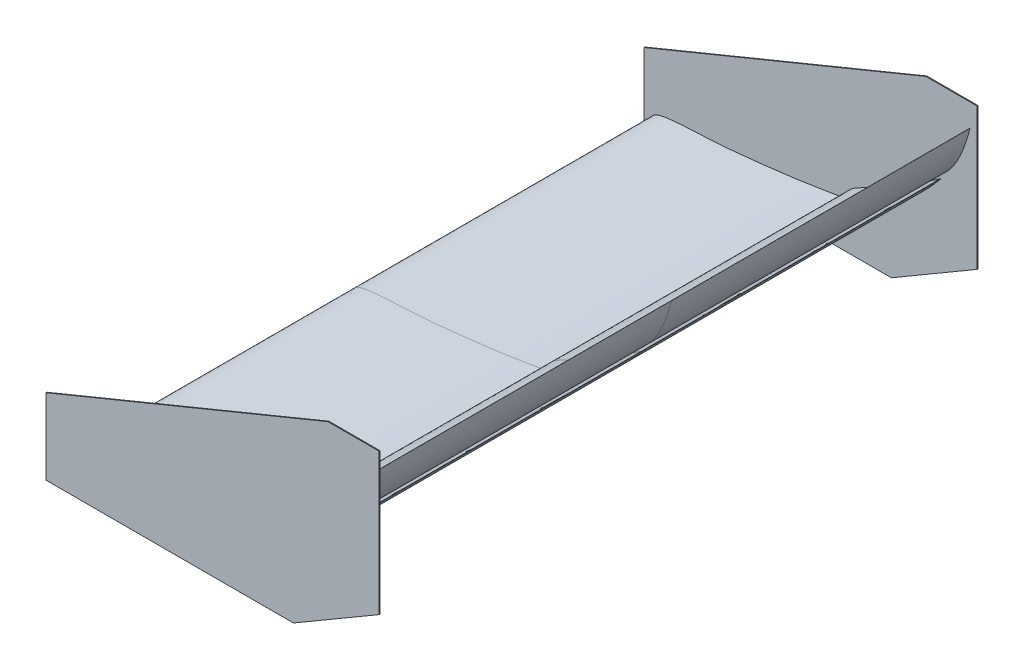
SolidWorks part; units mm, degrees
ref_plane "Front Plane" through (0, 0, 0) normal (0, 0, 1) x (1, 0, 0)
ref_plane "Top Plane" through (0, 0, 0) normal (0, 1, 0) x (1, 0, 0)
ref_plane "Right Plane" through (0, 0, 0) normal (1, 0, 0) x (0, 0, -1)
curve "Curve1"
  spline degree 3 poles (99.0688, 13.798, 0) (98.985, 13.7552, 0) (98.6508, 13.5849, 0) (97.9029, 13.2032, 0) (96.6609, 12.5823, 0) (94.9376, 11.7325, 0) (92.7448, 10.6803, 0) (90.1008, 9.4515, 0) (87.0291, 8.0763, 0) (83.5562, 6.5881, 0) (79.7145, 5.0216, 0) (75.5395, 3.4142, 0) (71.0738, 1.7976, 0) (66.3611, 0.21, 0) (61.4497, -1.3148, 0) (56.392, -2.7475, 0) (51.2426, -4.0574, 0) (46.0551, -5.2184, 0) (40.854, -6.233, 0) (35.6813, -6.9933, 0) (30.6038, -7.449, 0) (25.7295, -7.6105, 0) (21.1262, -7.4993, 0) (16.8578, -7.1394, 0) (12.9825, -6.5696, 0) (9.5507, -5.8327, 0) (6.6043, -4.9721, 0) (4.1763, -4.0324, 0) (2.283, -3.0565, 0) (0.9373, -2.0695, 0) (0.1025, -1.073, 0) (-0.1138, 0.0176, 0) (0.4141, 0.9898, 0) (1.479, 1.7019, 0) (2.9987, 2.2847, 0) (4.9955, 2.7588, 0) (7.4464, 3.142, 0) (10.3255, 3.4469, 0) (13.5973, 3.6931, 0) (17.225, 3.9006, 0) (21.1689, 4.0985, 0) (25.3897, 4.3118, 0) (29.8469, 4.5676, 0) (34.499, 4.8945, 0) (39.3394, 5.3285, 0) (44.3266, 5.8555, 0) (49.4192, 6.3918, 0) (54.5234, 6.9659, 0) (59.5819, 7.5731, 0) (64.5401, 8.2118, 0) (69.3432, 8.8764, 0) (73.9381, 9.5566, 0) (78.2741, 10.2373, 0) (82.3012, 10.9094, 0) (85.9747, 11.5481, 0) (89.2527, 12.1455, 0) (92.092, 12.6747, 0) (94.4753, 13.1478, 0) (96.3297, 13.4752, 0) (97.7415, 13.8436, 0) (98.4673, 13.8401, 0) (98.9864, 14.1185, 0) (99.0172, 13.9649, 0) (99.0268, 13.9173, 0) knots 0 0 0 0 0.001372 0.005465 0.012235 0.021602 0.033461 0.047671 0.064081 0.082496 0.102719 0.124527 0.147676 0.171913 0.196978 0.222597 0.248497 0.274385 0.300041 0.32569 0.350525 0.37428 0.396711 0.417577 0.436654 0.453744 0.46868 0.481329 0.491631 0.499616 0.505546 0.510185 0.514824 0.520702 0.528516 0.538466 0.550543 0.564643 0.580638 0.598345 0.617584 0.638174 0.659922 0.682632 0.706121 0.730727 0.7557 0.780732 0.805564 0.829932 0.85357 0.876213 0.89761 0.917519 0.935698 0.951943 0.966047 0.97784 0.987174 0.993932 0.998018 0.999386 1 1 1 1
sketch "Sketch1" plane through (0, 0, 0) normal (0, 0, 1) x (1, 0, 0)
  line L0 (99.0268, 13.9173) -> (99.0688, 13.798)
  spline S0 degree 3 poles (-1512.6726, 3670.5274) (216.2288, 66.9665) (155.9525, 42.8322) (97.9029, 13.2032) (96.6609, 12.5823) (94.9376, 11.7325) (92.7448, 10.6803) (90.1008, 9.4515) (87.0291, 8.0763) (83.5562, 6.5881) (79.7145, 5.0216) (75.5395, 3.4142) (71.0738, 1.7976) (66.3611, 0.21) (61.4497, -1.3148) (56.392, -2.7475) (51.2426, -4.0574) (46.0551, -5.2184) (40.854, -6.233) (35.6813, -6.9933) (30.6038, -7.449) (25.7295, -7.6105) (21.1262, -7.4993) (16.8578, -7.1394) (12.9825, -6.5696) (9.5507, -5.8327) (6.6043, -4.9721) (4.1763, -4.0324) (2.283, -3.0565) (0.9373, -2.0695) (0.1025, -1.073) (-0.1138, 0.0176) (0.4141, 0.9898) (1.479, 1.7019) (2.9987, 2.2847) (4.9955, 2.7588) (7.4464, 3.142) (10.3255, 3.4469) (13.5973, 3.6931) (17.225, 3.9006) (21.1689, 4.0985) (25.3897, 4.3118) (29.8469, 4.5676) (34.499, 4.8945) (39.3394, 5.3285) (44.3266, 5.8555) (49.4192, 6.3918) (54.5234, 6.9659) (59.5819, 7.5731) (64.5401, 8.2118) (69.3432, 8.8764) (73.9381, 9.5566) (78.2741, 10.2373) (82.3012, 10.9094) (85.9747, 11.5481) (89.2527, 12.1455) (92.092, 12.6747) (94.4753, 13.1478) (96.3297, 13.4752) (97.7415, 13.8436) (98.4673, 13.8401) (101.7659, 15.6087) (62.7437, -56.794) (2072.5985, 3482.5615) knots -0.937364 -0.937364 -0.937364 -0.937364 0.001372 0.005465 0.012235 0.021602 0.033461 0.047671 0.064081 0.082496 0.102719 0.124527 0.147676 0.171913 0.196978 0.222597 0.248497 0.274385 0.300041 0.32569 0.350525 0.37428 0.396711 0.417577 0.436654 0.453744 0.46868 0.481329 0.491631 0.499616 0.505546 0.510185 0.514824 0.520702 0.528516 0.538466 0.550543 0.564643 0.580638 0.598345 0.617584 0.638174 0.659922 0.682632 0.706121 0.730727 0.7557 0.780732 0.805564 0.829932 0.85357 0.876213 0.89761 0.917519 0.935698 0.951943 0.966047 0.97784 0.987174 0.993932 0.998018 0.999386 1.032494 1.032494 1.032494 1.032494 only from (99.0688, 13.798) to (99.0268, 13.9173) construction
  spline S1 degree 3 poles (99.0688, 13.798) (98.985, 13.7552) (98.6508, 13.5849) (97.9029, 13.2032) (96.6609, 12.5823) (94.9376, 11.7325) (92.7448, 10.6803) (90.1008, 9.4515) (87.0291, 8.0763) (83.5562, 6.5881) (79.7145, 5.0216) (75.5395, 3.4142) (71.0738, 1.7976) (66.3611, 0.21) (61.4497, -1.3148) (56.392, -2.7475) (51.2426, -4.0574) (46.0551, -5.2184) (40.854, -6.233) (35.6813, -6.9933) (30.6038, -7.449) (25.7295, -7.6105) (21.1262, -7.4993) (16.8578, -7.1394) (12.9825, -6.5696) (9.5507, -5.8327) (6.6043, -4.9721) (4.1763, -4.0324) (2.283, -3.0565) (0.9373, -2.0695) (0.1025, -1.073) (-0.1138, 0.0176) (0.4141, 0.9898) (1.479, 1.7019) (2.9987, 2.2847) (4.9955, 2.7588) (7.4464, 3.142) (10.3255, 3.4469) (13.5973, 3.6931) (17.225, 3.9006) (21.1689, 4.0985) (25.3897, 4.3118) (29.8469, 4.5676) (34.499, 4.8945) (39.3394, 5.3285) (44.3266, 5.8555) (49.4192, 6.3918) (54.5234, 6.9659) (59.5819, 7.5731) (64.5401, 8.2118) (69.3432, 8.8764) (73.9381, 9.5566) (78.2741, 10.2373) (82.3012, 10.9094) (85.9747, 11.5481) (89.2527, 12.1455) (92.092, 12.6747) (94.4753, 13.1478) (96.3297, 13.4752) (97.7415, 13.8436) (98.4673, 13.8401) (98.9864, 14.1185) (99.0172, 13.9649) (99.0268, 13.9173) knots 0 0 0 0 0.001372 0.005465 0.012235 0.021602 0.033461 0.047671 0.064081 0.082496 0.102719 0.124527 0.147676 0.171913 0.196978 0.222597 0.248497 0.274385 0.300041 0.32569 0.350525 0.37428 0.396711 0.417577 0.436654 0.453744 0.46868 0.481329 0.491631 0.499616 0.505546 0.510185 0.514824 0.520702 0.528516 0.538466 0.550543 0.564643 0.580638 0.598345 0.617584 0.638174 0.659922 0.682632 0.706121 0.730727 0.7557 0.780732 0.805564 0.829932 0.85357 0.876213 0.89761 0.917519 0.935698 0.951943 0.966047 0.97784 0.987174 0.993932 0.998018 0.999386 1 1 1 1
extrude "Boss-Extrude1" add sketch "Sketch1" along normal blind 138.1
curve "Curve2"
  spline degree 3 poles (133.4459, 41.95, 0) (133.4162, 41.9134, 0) (133.2983, 41.7677, 0) (133.0343, 41.4412, 0) (132.5932, 40.905, 0) (131.9789, 40.1664, 0) (131.1913, 39.2398, 0) (130.2335, 38.1408, 0) (129.11, 36.888, 0) (127.8264, 35.5019, 0) (126.3902, 34.0051, 0) (124.81, 32.4219, 0) (123.099, 30.7753, 0) (121.2692, 29.0916, 0) (119.3359, 27.3964, 0) (117.3171, 25.7134, 0) (115.2314, 24.0678, 0) (113.098, 22.4825, 0) (110.9286, 20.9614, 0) (108.7205, 19.5621, 0) (106.4939, 18.3214, 0) (104.3003, 17.2563, 0) (102.175, 16.3709, 0) (100.1521, 15.6673, 0) (98.2661, 15.1394, 0) (96.5487, 14.7781, 0) (95.0278, 14.572, 0) (93.7277, 14.5074, 0) (92.6644, 14.5682, 0) (91.849, 14.7453, 0) (91.265, 15.0307, 0) (90.9445, 15.4849, 0) (90.9878, 16.0363, 0) (91.3294, 16.5781, 0) (91.9051, 17.1534, 0) (92.7207, 17.7761, 0) (93.7623, 18.4495, 0) (95.0154, 19.1743, 0) (96.4598, 19.9522, 0) (98.0746, 20.7847, 0) (99.8359, 21.6772, 0) (101.7205, 22.633, 0) (103.7043, 23.6562, 0) (105.7628, 24.7517, 0) (107.8855, 25.9343, 0) (110.0564, 27.1892, 0) (112.2734, 28.4699, 0) (114.4881, 29.7702, 0) (116.6752, 31.0763, 0) (118.8101, 32.3763, 0) (120.8689, 33.6567, 0) (122.8294, 34.9019, 0) (124.6715, 36.0946, 0) (126.3743, 37.2206, 0) (127.9224, 38.2594, 0) (129.2982, 39.1989, 0) (130.4875, 40.018, 0) (131.4799, 40.7188, 0) (132.2604, 41.2455, 0) (132.8303, 41.7009, 0) (133.1625, 41.8469, 0) (133.343, 42.0796, 0) (133.3884, 42.0158, 0) (133.4024, 41.996, 0) knots 0 0 0 0 0.001372 0.005465 0.012235 0.021602 0.033461 0.047671 0.064081 0.082496 0.102719 0.124527 0.147676 0.171913 0.196978 0.222597 0.248497 0.274385 0.300041 0.32569 0.350525 0.37428 0.396711 0.417577 0.436654 0.453744 0.46868 0.481329 0.491631 0.499616 0.505546 0.510185 0.514824 0.520702 0.528516 0.538466 0.550543 0.564643 0.580638 0.598345 0.617584 0.638174 0.659922 0.682632 0.706121 0.730727 0.7557 0.780732 0.805564 0.829932 0.85357 0.876213 0.89761 0.917519 0.935698 0.951943 0.966047 0.97784 0.987174 0.993932 0.998018 0.999386 1 1 1 1
sketch "Sketch2" plane through (0, 0, 0) normal (0, 0, 1) x (1, 0, 0)
  line L0 (133.4022, 41.9963) -> (133.4459, 41.95)
  spline S0 degree 3 poles (-2110.8187, 2030.7967) (182.5864, 96.5513) (156.3853, 70.3189) (133.0343, 41.4412) (132.5932, 40.905) (131.9789, 40.1664) (131.1913, 39.2398) (130.2335, 38.1408) (129.11, 36.888) (127.8264, 35.5019) (126.3902, 34.0051) (124.81, 32.4219) (123.099, 30.7753) (121.2692, 29.0916) (119.3359, 27.3964) (117.3171, 25.7134) (115.2314, 24.0678) (113.098, 22.4825) (110.9286, 20.9614) (108.7205, 19.5621) (106.4939, 18.3214) (104.3003, 17.2563) (102.175, 16.3709) (100.1521, 15.6673) (98.2661, 15.1394) (96.5487, 14.7781) (95.0278, 14.572) (93.7277, 14.5074) (92.6644, 14.5682) (91.849, 14.7453) (91.265, 15.0307) (90.9445, 15.4849) (90.9878, 16.0363) (91.3294, 16.5781) (91.9051, 17.1534) (92.7207, 17.7761) (93.7623, 18.4495) (95.0154, 19.1743) (96.4598, 19.9522) (98.0746, 20.7847) (99.8359, 21.6772) (101.7205, 22.633) (103.7043, 23.6562) (105.7628, 24.7517) (107.8855, 25.9343) (110.0564, 27.1892) (112.2734, 28.4699) (114.4881, 29.7702) (116.6752, 31.0763) (118.8101, 32.3763) (120.8689, 33.6567) (122.8294, 34.9019) (124.6715, 36.0946) (126.3743, 37.2206) (127.9224, 38.2594) (129.2982, 39.1989) (130.4875, 40.018) (131.4799, 40.7188) (132.2604, 41.2455) (132.8303, 41.7009) (133.1625, 41.8469) (134.4499, 43.5066) (130.284, -9.7014) (427.082, 3025.7492) knots -1.069969 -1.069969 -1.069969 -1.069969 0.001372 0.005465 0.012235 0.021602 0.033461 0.047671 0.064081 0.082496 0.102719 0.124527 0.147676 0.171913 0.196978 0.222597 0.248497 0.274385 0.300041 0.32569 0.350525 0.37428 0.396711 0.417577 0.436654 0.453744 0.46868 0.481329 0.491631 0.499616 0.505546 0.510185 0.514824 0.520702 0.528516 0.538466 0.550543 0.564643 0.580638 0.598345 0.617584 0.638174 0.659922 0.682632 0.706121 0.730727 0.7557 0.780732 0.805564 0.829932 0.85357 0.876213 0.89761 0.917519 0.935698 0.951943 0.966047 0.97784 0.987174 0.993932 0.998018 0.999386 1.037213 1.037213 1.037213 1.037213 only from (133.4459, 41.95) to (133.4024, 41.996) construction
  spline S1 degree 3 poles (133.4459, 41.95) (133.4162, 41.9134) (133.2983, 41.7677) (133.0343, 41.4412) (132.5932, 40.905) (131.9789, 40.1664) (131.1913, 39.2398) (130.2335, 38.1408) (129.11, 36.888) (127.8264, 35.5019) (126.3902, 34.0051) (124.81, 32.4219) (123.099, 30.7753) (121.2692, 29.0916) (119.3359, 27.3964) (117.3171, 25.7134) (115.2314, 24.0678) (113.098, 22.4825) (110.9286, 20.9614) (108.7205, 19.5621) (106.4939, 18.3214) (104.3003, 17.2563) (102.175, 16.3709) (100.1521, 15.6673) (98.2661, 15.1394) (96.5487, 14.7781) (95.0278, 14.572) (93.7277, 14.5074) (92.6644, 14.5682) (91.849, 14.7453) (91.265, 15.0307) (90.9445, 15.4849) (90.9878, 16.0363) (91.3294, 16.5781) (91.9051, 17.1534) (92.7207, 17.7761) (93.7623, 18.4495) (95.0154, 19.1743) (96.4598, 19.9522) (98.0746, 20.7847) (99.8359, 21.6772) (101.7205, 22.633) (103.7043, 23.6562) (105.7628, 24.7517) (107.8855, 25.9343) (110.0564, 27.1892) (112.2734, 28.4699) (114.4881, 29.7702) (116.6752, 31.0763) (118.8101, 32.3763) (120.8689, 33.6567) (122.8294, 34.9019) (124.6715, 36.0946) (126.3743, 37.2206) (127.9224, 38.2594) (129.2982, 39.1989) (130.4875, 40.018) (131.4799, 40.7188) (132.2604, 41.2455) (132.8303, 41.7009) (133.1625, 41.8469) (133.343, 42.0796) (133.3884, 42.0158) (133.4024, 41.996) knots 0 0 0 0 0.001372 0.005465 0.012235 0.021602 0.033461 0.047671 0.064081 0.082496 0.102719 0.124527 0.147676 0.171913 0.196978 0.222597 0.248497 0.274385 0.300041 0.32569 0.350525 0.37428 0.396711 0.417577 0.436654 0.453744 0.46868 0.481329 0.491631 0.499616 0.505546 0.510185 0.514824 0.520702 0.528516 0.538466 0.550543 0.564643 0.580638 0.598345 0.617584 0.638174 0.659922 0.682632 0.706121 0.730727 0.7557 0.780732 0.805564 0.829932 0.85357 0.876213 0.89761 0.917519 0.935698 0.951943 0.966047 0.97784 0.987174 0.993932 0.998018 0.999386 1 1 1 1
extrude "Boss-Extrude2" add sketch "Sketch2" along normal blind 138.1 separate body
curve "Curve3"
  spline degree 3 poles (146.9331, 68.9281, 0) (146.9268, 68.9006, 0) (146.9015, 68.7909, 0) (146.845, 68.5454, 0) (146.7482, 68.1403, 0) (146.6111, 67.5804, 0) (146.4301, 66.8735, 0) (146.2026, 66.029, 0) (145.9263, 65.0578, 0) (145.5986, 63.9728, 0) (145.2178, 62.7878, 0) (144.7821, 61.5184, 0) (144.2925, 60.1804, 0) (143.7486, 58.7911, 0) (143.1519, 57.3684, 0) (142.5058, 55.9298, 0) (141.8139, 54.4938, 0) (141.0803, 53.0778, 0) (140.3106, 51.6869, 0) (139.4878, 50.3515, 0) (138.6134, 49.0967, 0) (137.7106, 47.9454, 0) (136.7973, 46.909, 0) (135.8915, 45.9974, 0) (135.0133, 45.2167, 0) (134.1821, 44.5701, 0) (133.4162, 44.0589, 0) (132.732, 43.6822, 0) (132.1427, 43.4353, 0) (131.6564, 43.3163, 0) (131.2664, 43.3166, 0) (130.974, 43.4772, 0) (130.8524, 43.786, 0) (130.8941, 44.1681, 0) (131.0532, 44.6297, 0) (131.3293, 45.18, 0) (131.7138, 45.8172, 0) (132.199, 46.5376, 0) (132.7733, 47.337, 0) (133.4252, 48.2107, 0) (134.1402, 49.1552, 0) (134.9052, 50.1664, 0) (135.7059, 51.24, 0) (136.5278, 52.3722, 0) (137.3615, 53.5683, 0) (138.2021, 54.816, 0) (139.0609, 56.0898, 0) (139.9132, 57.3735, 0) (140.7491, 58.6531, 0) (141.5585, 59.9157, 0) (142.332, 61.1477, 0) (143.0617, 62.3348, 0) (143.7414, 63.4625, 0) (144.3635, 64.5176, 0) (144.9251, 65.485, 0) (145.42, 66.3535, 0) (145.8459, 67.1081, 0) (146.1967, 67.7471, 0) (146.4791, 68.2364, 0) (146.6667, 68.6318, 0) (146.8074, 68.798, 0) (146.8436, 68.9709, 0) (146.8848, 68.9484, 0) (146.8976, 68.9414, 0) knots 0 0 0 0 0.001372 0.005465 0.012235 0.021602 0.033461 0.047671 0.064081 0.082496 0.102719 0.124527 0.147676 0.171913 0.196978 0.222597 0.248497 0.274385 0.300041 0.32569 0.350525 0.37428 0.396711 0.417577 0.436654 0.453744 0.46868 0.481329 0.491631 0.499616 0.505546 0.510185 0.514824 0.520701 0.528516 0.538466 0.550543 0.564643 0.580638 0.598345 0.617584 0.638174 0.659922 0.682632 0.706121 0.730727 0.7557 0.780732 0.805564 0.829932 0.85357 0.876213 0.89761 0.917519 0.935698 0.951943 0.966047 0.97784 0.987174 0.993931 0.998018 0.999386 1 1 1 1
sketch "Sketch3" plane through (0, 0, 0) normal (0, 0, 1) x (1, 0, 0)
  line L0 (146.8976, 68.9414) -> (146.9331, 68.9281)
  spline S0 degree 3 poles (-2751.2246, 841.2815) (161.7759, 118.7711) (152.7275, 94.108) (146.845, 68.5454) (146.7482, 68.1403) (146.6111, 67.5804) (146.4301, 66.8735) (146.2026, 66.029) (145.9263, 65.0578) (145.5986, 63.9728) (145.2178, 62.7878) (144.7821, 61.5184) (144.2925, 60.1804) (143.7486, 58.7911) (143.1519, 57.3684) (142.5058, 55.9298) (141.8139, 54.4938) (141.0803, 53.0778) (140.3106, 51.6869) (139.4878, 50.3515) (138.6134, 49.0967) (137.7106, 47.9454) (136.7973, 46.909) (135.8915, 45.9974) (135.0133, 45.2167) (134.1821, 44.5701) (133.4162, 44.0589) (132.732, 43.6822) (132.1427, 43.4353) (131.6564, 43.3163) (131.2664, 43.3166) (130.974, 43.4772) (130.8524, 43.786) (130.8941, 44.1681) (131.0532, 44.6297) (131.3293, 45.18) (131.7138, 45.8172) (132.199, 46.5376) (132.7733, 47.337) (133.4252, 48.2107) (134.1402, 49.1552) (134.9052, 50.1664) (135.7059, 51.24) (136.5278, 52.3722) (137.3615, 53.5683) (138.2021, 54.816) (139.0609, 56.0898) (139.9132, 57.3735) (140.7491, 58.6531) (141.5585, 59.9157) (142.332, 61.1477) (143.0617, 62.3348) (143.7414, 63.4625) (144.3635, 64.5176) (144.9251, 65.485) (145.42, 66.3535) (145.8459, 67.1081) (146.1967, 67.7471) (146.4791, 68.2364) (146.6667, 68.6318) (146.8074, 68.798) (147.1062, 70.2281) (163.3026, 28.806) (-897.268, 2877.4458) knots -1.261722 -1.261722 -1.261722 -1.261722 0.001372 0.005465 0.012235 0.021602 0.033461 0.047671 0.064081 0.082496 0.102719 0.124527 0.147676 0.171913 0.196978 0.222597 0.248497 0.274385 0.300041 0.32569 0.350525 0.37428 0.396711 0.417577 0.436654 0.453744 0.46868 0.481329 0.491631 0.499616 0.505546 0.510185 0.514824 0.520701 0.528516 0.538466 0.550543 0.564643 0.580638 0.598345 0.617584 0.638174 0.659922 0.682632 0.706121 0.730727 0.7557 0.780732 0.805564 0.829932 0.85357 0.876213 0.89761 0.917519 0.935698 0.951943 0.966047 0.97784 0.987174 0.993931 0.998018 0.999386 1.044107 1.044107 1.044107 1.044107 only from (146.9331, 68.9281) to (146.8976, 68.9414) construction
  spline S1 degree 3 poles (146.9331, 68.9281) (146.9268, 68.9006) (146.9015, 68.7909) (146.845, 68.5454) (146.7482, 68.1403) (146.6111, 67.5804) (146.4301, 66.8735) (146.2026, 66.029) (145.9263, 65.0578) (145.5986, 63.9728) (145.2178, 62.7878) (144.7821, 61.5184) (144.2925, 60.1804) (143.7486, 58.7911) (143.1519, 57.3684) (142.5058, 55.9298) (141.8139, 54.4938) (141.0803, 53.0778) (140.3106, 51.6869) (139.4878, 50.3515) (138.6134, 49.0967) (137.7106, 47.9454) (136.7973, 46.909) (135.8915, 45.9974) (135.0133, 45.2167) (134.1821, 44.5701) (133.4162, 44.0589) (132.732, 43.6822) (132.1427, 43.4353) (131.6564, 43.3163) (131.2664, 43.3166) (130.974, 43.4772) (130.8524, 43.786) (130.8941, 44.1681) (131.0532, 44.6297) (131.3293, 45.18) (131.7138, 45.8172) (132.199, 46.5376) (132.7733, 47.337) (133.4252, 48.2107) (134.1402, 49.1552) (134.9052, 50.1664) (135.7059, 51.24) (136.5278, 52.3722) (137.3615, 53.5683) (138.2021, 54.816) (139.0609, 56.0898) (139.9132, 57.3735) (140.7491, 58.6531) (141.5585, 59.9157) (142.332, 61.1477) (143.0617, 62.3348) (143.7414, 63.4625) (144.3635, 64.5176) (144.9251, 65.485) (145.42, 66.3535) (145.8459, 67.1081) (146.1967, 67.7471) (146.4791, 68.2364) (146.6667, 68.6318) (146.8074, 68.798) (146.8436, 68.9709) (146.8848, 68.9484) (146.8976, 68.9414) knots 0 0 0 0 0.001372 0.005465 0.012235 0.021602 0.033461 0.047671 0.064081 0.082496 0.102719 0.124527 0.147676 0.171913 0.196978 0.222597 0.248497 0.274385 0.300041 0.32569 0.350525 0.37428 0.396711 0.417577 0.436654 0.453744 0.46868 0.481329 0.491631 0.499616 0.505546 0.510185 0.514824 0.520701 0.528516 0.538466 0.550543 0.564643 0.580638 0.598345 0.617584 0.638174 0.659922 0.682632 0.706121 0.730727 0.7557 0.780732 0.805564 0.829932 0.85357 0.876213 0.89761 0.917519 0.935698 0.951943 0.966047 0.97784 0.987174 0.993931 0.998018 0.999386 1 1 1 1
extrude "Boss-Extrude3" add sketch "Sketch3" along normal blind 138.1 separate body
scale "Scale1" bodies to scale 101 102 103 scale about origin uniform scaling yes scale factor 5
ref_plane "Plane1" through (0, 0, 690.5) normal (0, 0, 1) x (1, 0, 0)
sketch "Sketch5" plane through (0, 0, 690.5) normal (0, 0, 1) x (1, 0, 0)
  line L0 (-19.2839, 129.8205) -> (632.9942, 397.9277)
  line L1 (-19.2839, -45.4357) -> (552.9102, -45.4357)
  line L2 (-19.2839, -45.4357) -> (-19.2839, 129.8205)
  line L3 (632.9942, 397.9277) -> (751.3792, 397.9277)
  line L4 (751.3792, 70.628) -> (751.3792, 397.9277)
  line L5 (-19.2839, -45.4357) -> (751.3792, 397.9277) construction
  line L6 (-19.2839, 397.9277) -> (751.3792, -45.4357) construction
  line L7 (552.9102, -45.4357) -> (751.3792, 70.628)
  point P4 (366.0476, 176.246)
extrude "Boss-Extrude4" add sketch "Sketch5" along normal blind 2 separate body
mirror "Mirror1" about plane through (0, 0, 0) normal (0, 0, 1) of bodies 106 105 104 107
